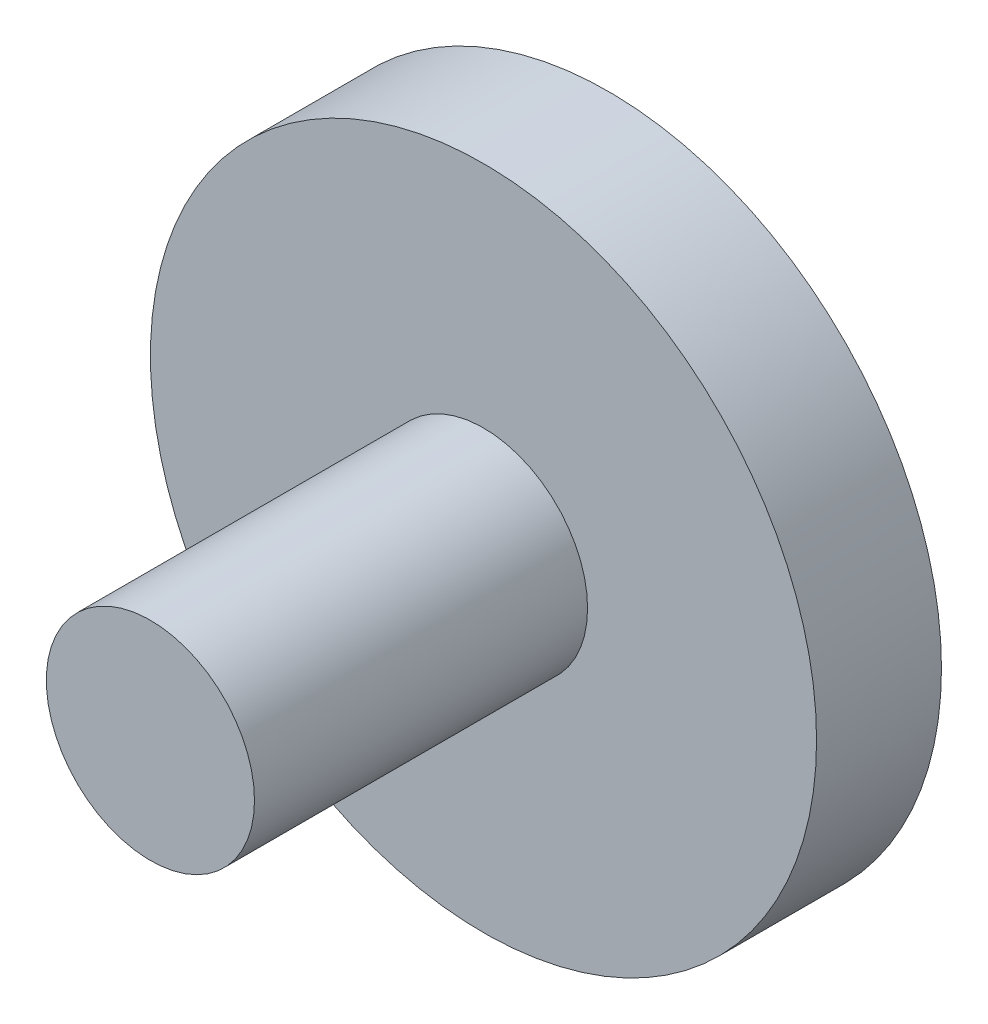
SolidWorks part; units mm, degrees
ref_plane "Front Plane" through (0, 0, 0) normal (0, 0, 1) x (1, 0, 0)
ref_plane "Top Plane" through (0, 0, 0) normal (0, 1, 0) x (1, 0, 0)
ref_plane "Right Plane" through (0, 0, 0) normal (1, 0, 0) x (0, 0, -1)
sketch "S01 - Low flanged head" plane through (0, 0, 0) normal (0, 0, 1) x (1, 0, 0)
  circle A0 centre (0, 0) radius 8
  dimension "D1" = 16
extrude "01 - Low flanged head" add sketch "S01 - Low flanged head" along normal blind 3 from offset 3
sketch "S02 - M5 thread major diameter" plane through (0, 0, 0) normal (0, 0, 1) x (1, 0, 0)
  circle A0 centre (0, 0) radius 2.5
  dimension "D1" = 5
extrude "02 - M5 thread major diameter" add sketch "S02 - M5 thread major diameter" along normal blind 8
sketch "S03 - Drive hex" plane through (0, 0, 0) normal (0, 0, 1) x (1, 0, 0)
  line L0 (1.7321, 0) -> (0.866, 1.5)
  line L1 (0.866, 1.5) -> (-0.866, 1.5)
  line L2 (-0.866, 1.5) -> (-1.7321, 0)
  line L3 (-1.7321, 0) -> (-0.866, -1.5)
  line L4 (-0.866, -1.5) -> (0.866, -1.5)
  line L5 (0.866, -1.5) -> (1.7321, 0)
  dimension "D1" = 0.866
  dimension "D2" = 1.7321
  dimension "D3" = 0.866
  dimension "D4" = 1.7321
  dimension "D5" = 1.5
  dimension "D6" = 1.5
extrude "03 - Drive hex" cut sketch "S03 - Drive hex" along normal blind 1.7 from offset 3.1
